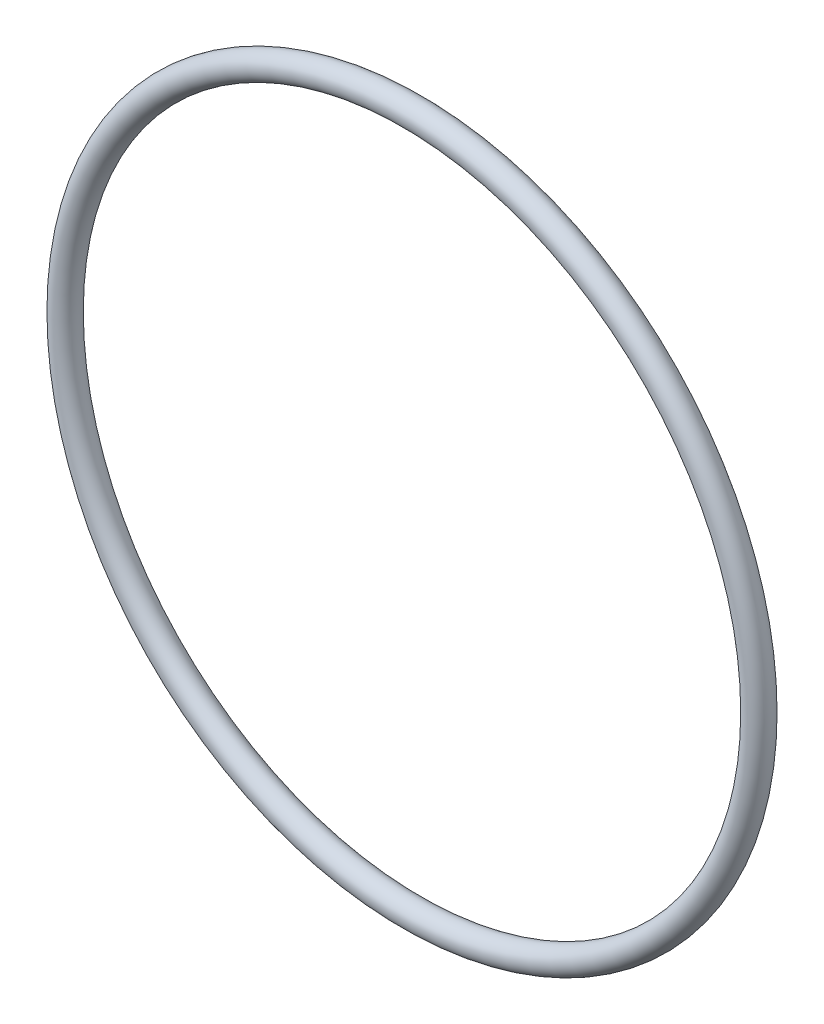
SolidWorks part; units mm, degrees
ref_plane "Front" through (0, 0, 0) normal (0, 0, 1) x (1, 0, 0)
ref_plane "Top" through (0, 0, 0) normal (0, 1, 0) x (1, 0, 0)
ref_plane "Right" through (0, 0, 0) normal (1, 0, 0) x (0, 0, -1)
sketch "Sketch1" plane through (0, 0, 0) normal (1, 0, 0) x (0, -1, 0)
  line L0 (0, -1.3081) -> (0, 1.3081) construction
  line L2 (-40.2476, 0) -> (40.2476, 0) construction
  line L3 (-33.9725, 0) -> (33.9725, 0) construction
  circle A0 centre (35.2806, 0) radius 1.3081
  point P9 (33.9725, 0)
  point P10 (36.5887, 0)
  point P13 (35.2806, 1.3081)
  point P14 (35.2806, -1.3081)
  dimension "Width" = 2.6162
  dimension "ID" = 67.945
revolve "Revolve1" add sketch "Sketch1" angle 360 about L0
